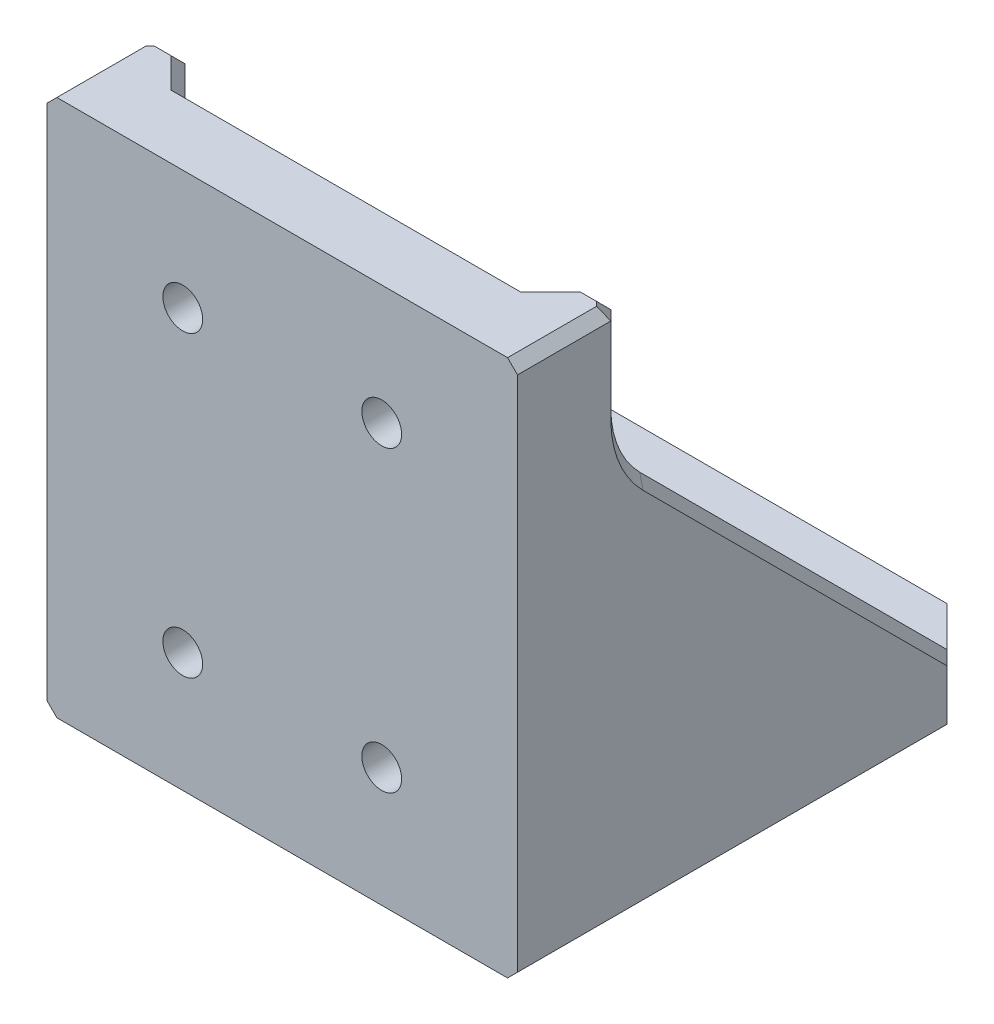
SolidWorks part; units mm, degrees
ref_plane "Front Plane" through (0, 0, 0) normal (0, 0, 1) x (1, 0, 0)
ref_plane "Top Plane" through (0, 0, 0) normal (0, 1, 0) x (1, 0, 0)
ref_plane "Right Plane" through (0, 0, 0) normal (1, 0, 0) x (0, 0, -1)
sketch "Sketch1" plane through (0, 0, 0) normal (0, 1, 0) x (1, 0, 0)
  line L0 (-21.15, 17.15) -> (-17.15, 21.15)
  line L1 (-17.15, -21.15) -> (17.15, -21.15)
  line L2 (-21.15, -17.15) -> (-21.15, 17.15)
  line L3 (-17.15, 21.15) -> (17.15, 21.15)
  line L4 (21.15, -17.15) -> (21.15, 17.15)
  line L5 (-21.15, -21.15) -> (21.15, 21.15) construction
  line L6 (-21.15, 21.15) -> (21.15, -21.15) construction
  line L7 (-21.15, -17.15) -> (-17.15, -21.15)
  line L8 (17.15, -21.15) -> (21.15, -17.15)
  line L9 (17.15, 21.15) -> (21.15, 17.15)
  circle A0 centre (-15.5, 15.5) radius 1.5
  circle A1 centre (15.5, 15.5) radius 1.5
  circle A2 centre (15.5, -15.5) radius 1.5
  circle A3 centre (-15.5, -15.5) radius 1.5
  circle A4 centre (0, 0) radius 11.5
  point P0 (0, 0)
  dimension "D3" = 3
  dimension "D4" = 3
  dimension "D9" = 3
  dimension "D10" = 3
  dimension "D12" = 23
  dimension "D1" = 42.3
  dimension "D2" = 42.3
  dimension "D11" = 31
extrude "Boss-Extrude1" add sketch "Sketch1" along normal blind 5
sketch "Sketch5" plane through (0, 0, 0) normal (0, 1, 0) x (1, 0, 0)
  line L16 (-23.65, 18.1855) -> (-23.65, -18.1855)
  line L17 (-23.65, -18.1855) -> (-18.1855, -23.65)
  line L18 (-18.1855, -23.65) -> (18.1855, -23.65)
  line L19 (18.1855, -23.65) -> (23.65, -18.1855)
  line L20 (23.65, -18.1855) -> (23.65, 18.1855)
  line L21 (23.65, 18.1855) -> (18.1855, 23.65)
  line L22 (18.1855, 23.65) -> (-18.1855, 23.65)
  line L23 (-18.1855, 23.65) -> (-23.65, 18.1855)
  line L24 (-23.65, 14.65) -> (-23.65, -18.1855)
  line L25 (-23.65, -18.1855) -> (-18.1855, -23.65)
  line L26 (-18.1855, -23.65) -> (18.1855, -23.65)
  line L27 (18.1855, -23.65) -> (23.65, -18.1855)
  line L28 (23.65, -18.1855) -> (23.65, 14.65)
  line L29 (23.65, 18.1855) -> (18.1855, 23.65) construction
  line L30 (18.1855, 23.65) -> (-18.1855, 23.65) construction
  line L31 (-18.1855, 23.65) -> (-23.65, 18.1855) construction
  line L32 (-21.15, 17.15) -> (-23.65, 14.65)
  line L33 (21.15, 17.15) -> (23.65, 14.65)
  line L34 (-23.65, 18.1855) -> (-23.65, 14.65) construction
  line L35 (23.65, 14.65) -> (23.65, 18.1855) construction
  line L40 (-21.15, 17.15) -> (-21.15, -17.15)
  line L41 (-21.15, -17.15) -> (-17.15, -21.15)
  line L42 (-17.15, -21.15) -> (17.15, -21.15)
  line L43 (17.15, -21.15) -> (21.15, -17.15)
  line L44 (21.15, -17.15) -> (21.15, 17.15)
  line L45 (21.15, 17.15) -> (17.15, 21.15)
  line L46 (17.15, 21.15) -> (-17.15, 21.15)
  line L47 (-17.15, 21.15) -> (-21.15, 17.15)
  line L48 (-21.15, 17.15) -> (-21.15, -17.15)
  line L49 (-21.15, -17.15) -> (-17.15, -21.15)
  line L50 (-17.15, -21.15) -> (17.15, -21.15)
  line L51 (17.15, -21.15) -> (21.15, -17.15)
  line L52 (21.15, -17.15) -> (21.15, 17.15)
  line L53 (21.15, 17.15) -> (17.15, 21.15) construction
  line L54 (17.15, 21.15) -> (-17.15, 21.15) construction
  line L55 (-17.15, 21.15) -> (-21.15, 17.15) construction
  dimension "D1" = 2.5
  dimension "D2" = 0
extrude "Boss-Extrude2" add sketch "Sketch5" along normal blind 54
sketch "Sketch6" plane through (0, 0, 0) normal (1, 0, 0) x (0, 0, -1)
  line L0 (17.15, 5) -> (-18.15, 40.3)
  line L1 (-18.15, 40.3) -> (-18.15, 54)
  line L2 (-23.65, 54) -> (-18.1855, 54) construction
  line L3 (-18.15, 54) -> (17.15, 54)
  line L4 (17.15, 54) -> (17.15, 5)
  line L5 (-23.65, 54) -> (-23.65, 0) construction
  dimension "D1" = 5.5
  dimension "D2" = 45
extrude "Cut-Extrude1" cut sketch "Sketch6" against normal through all both and the other way through all
fillet "Fillet1" radius 10 2 edges at (-21.9, 40.3, 18.15) (21.9, 40.3, 18.15)
sketch "Sketch9" plane through (0, 0, 0) normal (0, 1, 0) x (1, 0, 0)
  line L0 (-18.1855, -23.65) -> (-21, -28.5248)
  line L1 (-21, -28.5248) -> (21, -28.5248)
  line L2 (21, -28.5248) -> (18.1855, -23.65)
  line L3 (18.1855, -23.65) -> (-18.1855, -23.65)
  dimension "D1" = 60
  dimension "D2" = 60
  dimension "D3" = 42
extrude "Boss-Extrude3" add sketch "Sketch9" along normal blind 51
chamfer "Chamfer2" distance 1 angle 45 1 edges at (0, 0, 11.5)
sketch "Sketch10" plane through (0, 54, 0) normal (0, 1, 0) x (1, 0, 0)
  line L0 (-23.65, -18.15) -> (-20.15, -18.15)
  line L1 (-20.15, -18.15) -> (-17.15, -21.15)
  line L2 (-17.15, -21.15) -> (17.15, -21.15)
  line L3 (17.15, -21.15) -> (20.15, -18.15)
  line L4 (20.15, -18.15) -> (23.65, -18.15)
  line L5 (23.65, -18.15) -> (23.65, -28.5248)
  line L6 (23.65, -28.5248) -> (-23.65, -28.5248)
  line L7 (-23.65, -28.5248) -> (-23.65, -18.15)
  line L10 (-21, -28.5248) -> (21, -28.5248) construction
extrude "Boss-Extrude4" add sketch "Sketch10" against normal up to surface (54 mm away) up to face at (0, 0, -12.5)
chamfer "Chamfer3" distance 1 angle 45 5 edges at (-23.65, 0, 6.9374) (23.65, 0, 6.9374) (20.4, 0, -17.9) (-20.4, 0, -17.9) (0, 0, -21.15)
chamfer "Chamfer4" distance 1 angle 45 6 edges at (-23.65, 49.2211, 18.15) (-23.65, 40.6153, 17.3888) (-23.65, 22.4355, 0.2855) (23.65, 49.2211, 18.15) (23.65, 40.6153, 17.3888) (23.65, 22.4355, 0.2855)
chamfer "Chamfer5" distance 1 angle 45 9 edges at (23.65, 54, 23.8374) (23.15, 54, 18.65) (21.4, 54, 18.15) (18.65, 54, 19.65) (-23.65, 54, 23.8374) (-23.15, 54, 18.65) (-21.4, 54, 18.15) (-18.65, 54, 19.65) (0, 54, 21.15)
sketch "Sketch11" plane through (0, 0, 21.15) normal (0, 0, -1) x (-1, 0, 0)
  line L0 (23.65, 1) -> (23.65, 53) construction
  line L1 (-10, 12) -> (10, 12) construction
  line L2 (-10, 12) -> (-10, 42) construction
  line L3 (-10, 42) -> (10, 42) construction
  line L4 (10, 12) -> (10, 42) construction
  line L5 (-10, 12) -> (10, 42) construction
  line L6 (-10, 42) -> (10, 12) construction
  circle A0 centre (-10, 42) radius 4
  circle A1 centre (10, 42) radius 4
  circle A2 centre (-10, 12) radius 4
  circle A3 centre (10, 12) radius 4
  point P0 (0, 27)
  point P7 (23.65, 27)
  dimension "D3" = 8
  dimension "D4" = 8
  dimension "D5" = 8
  dimension "D6" = 8
  dimension "D1" = 30
  dimension "D2" = 20
extrude "Cut-Extrude2" cut sketch "Sketch11" against normal blind 3
sketch "Sketch12" plane through (0, 0, 21.15) normal (0, 0, -1) x (-1, 0, 0)
  circle A0 centre (-10, 42) radius 2
  circle A1 centre (10, 42) radius 2
  circle A2 centre (-10, 12) radius 2
  circle A3 centre (10, 12) radius 2
  dimension "D1" = 4
  dimension "D2" = 4
  dimension "D3" = 4
  dimension "D4" = 4
extrude "Cut-Extrude3" cut sketch "Sketch12" against normal through all
chamfer "Chamfer6" distance 1 angle 45 4 edges at (-14, 12, 21.15) (6, 12, 21.15) (-14, 42, 21.15) (6, 42, 21.15)
